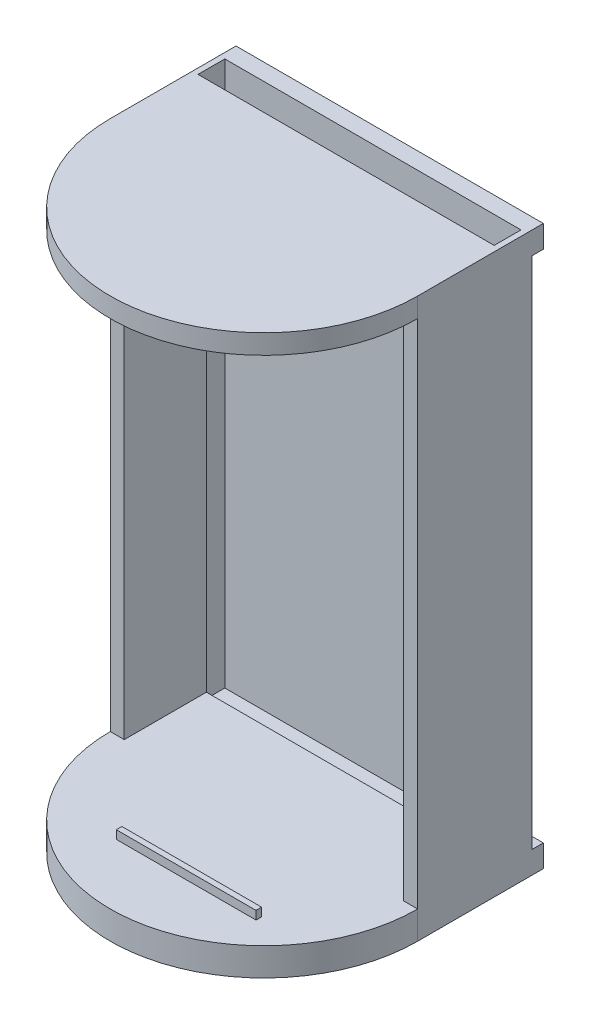
SolidWorks part; units mm, degrees
ref_plane "前基準面" through (0, 0, 0) normal (0, 0, 1) x (1, 0, 0)
ref_plane "上基準面" through (0, 0, 0) normal (0, 1, 0) x (1, 0, 0)
ref_plane "右基準面" through (0, 0, 0) normal (1, 0, 0) x (0, 0, -1)
sketch "草圖14" plane through (0, 0, 0) normal (0, 0, 1) x (1, 0, 0)
  line L0 (-52.3057, 82.5) -> (57.6943, 82.5)
  line L1 (57.6943, 82.5) -> (57.6943, -117.5)
  line L2 (57.6943, -117.5) -> (-52.3057, -117.5)
  line L3 (-52.3057, -117.5) -> (-52.3057, 82.5)
  dimension "D1" = 200
  dimension "D2" = 110
extrude "填料-伸長11" add sketch "草圖14" along normal blind 15
sketch "草圖15" plane through (0, 0, 15) normal (0, 0, 1) x (1, 0, 0)
  line L0 (-52.3057, 82.5) -> (-52.3057, -117.5)
  line L1 (-52.3057, -117.5) -> (-47.3057, -117.5)
  line L2 (57.6943, 82.5) -> (-52.3057, 82.5) construction
  line L3 (-47.3057, -117.5) -> (-47.3057, 82.5)
  line L4 (57.6943, -117.5) -> (57.6943, 82.5) construction
  line L5 (-47.3057, 82.5) -> (-52.3057, 82.5)
  line L6 (57.6943, 82.5) -> (52.6943, 82.5)
  line L7 (-52.3057, -117.5) -> (57.6943, -117.5) construction
  line L8 (52.6943, 82.5) -> (52.6943, -117.5)
  line L9 (-52.3057, 82.5) -> (-52.3057, -117.5) construction
  line L10 (52.6943, -117.5) -> (57.6943, -117.5)
  line L11 (57.6943, -117.5) -> (57.6943, 82.5)
  dimension "D4" = 5
extrude "填料-伸長12" add sketch "草圖15" along normal blind 30
sketch "草圖17" plane through (0, -117.5, 0) normal (0, -1, 0) x (1, 0, 0)
  line L0 (-52.3057, 15) -> (-52.3057, 45)
  line L1 (57.6943, 45) -> (57.6943, 15)
  line L3 (-52.3057, 45) -> (-52.3057, 0) construction
  line L4 (57.6943, 45) -> (57.6943, 0) construction
  line L6 (-52.3057, 15) -> (57.6943, 15)
  line L7 (-47.3057, 15) -> (52.6943, 15) construction
  arc A0 (-52.3057, 45) -> (57.6943, 45) centre (2.6943, 45) cw
extrude "填料-伸長14" add sketch "草圖17" against normal blind 10 separate body
sketch "草圖18" plane through (0, 82.5, 0) normal (0, 1, 0) x (1, 0, 0)
  line L0 (-52.3057, -15) -> (-52.3057, -45)
  line L1 (57.6943, -45) -> (57.6943, -15)
  line L2 (57.6943, -15) -> (-52.3057, -15)
  line L3 (52.6943, -15) -> (-47.3057, -15) construction
  line L4 (-52.3057, -45) -> (-52.3057, 0) construction
  arc A0 (-52.3057, -45) -> (57.6943, -45) centre (2.6943, -45) ccw
  arc A1 (-52.3057, -45) -> (57.6943, -45) centre (2.6943, -45) ccw construction
extrude "填料-伸長15" add sketch "草圖18" against normal blind 7
sketch "草圖19" plane through (-52.3057, 0, 0) normal (-1, 0, 0) x (0, 0, 1)
  line L0 (0, 74.5) -> (4, 74.5)
  line L1 (0, 82.5) -> (0, -117.5) construction
  line L2 (4, 74.5) -> (4, -109.5)
  line L3 (4, -109.5) -> (0, -109.5)
  line L4 (0, -109.5) -> (0, 74.5)
  line L5 (45, -117.5) -> (0, -117.5) construction
  line L6 (45, 82.5) -> (0, 82.5) construction
  dimension "D1" = 4
  dimension "D2" = 8
  dimension "D3" = 8
extrude "除料-伸長1" cut sketch "草圖19" against normal through all
sketch "草圖22" plane through (0, -107.5, 0) normal (0, 1, 0) x (1, 0, 0)
  line L0 (7.1943, -76.3382) -> (7.1943, -59.9645) construction
  line L1 (-17.8057, -75.3382) -> (32.1943, -75.3382)
  line L2 (-17.8057, -75.3382) -> (-17.8057, -77.3382)
  line L3 (-17.8057, -77.3382) -> (32.1943, -77.3382)
  line L4 (32.1943, -75.3382) -> (32.1943, -77.3382)
  line L5 (-17.8057, -75.3382) -> (32.1943, -77.3382) construction
  line L6 (-17.8057, -77.3382) -> (32.1943, -75.3382) construction
  line L7 (57.6943, -15) -> (57.6943, -45) construction
  point P0 (7.1943, -76.3382)
  dimension "D1" = 50
  dimension "D2" = 2
  dimension "D3" = 50.5
extrude "填料-伸長17" add sketch "草圖22" along normal blind 3
sketch "草圖23" plane through (0, 75.5, 0) normal (0, -1, 0) x (1, 0, 0)
  line L0 (-20.4013, 77.3382) -> (29.5987, 77.3382)
  line L1 (-20.4013, 77.3382) -> (-20.4013, 75.3382)
  line L2 (-20.4013, 75.3382) -> (29.5987, 75.3382)
  line L3 (29.5987, 77.3382) -> (29.5987, 75.3382)
  line L4 (-20.4013, 77.3382) -> (29.5987, 75.3382) construction
  line L5 (-20.4013, 75.3382) -> (29.5987, 77.3382) construction
  line L6 (-17.8057, 77.3382) -> (32.1943, 77.3382) construction
  line L7 (32.1943, 75.3382) -> (-17.8057, 75.3382) construction
  point P0 (4.5987, 76.3382)
extrude "填料-伸長18" add sketch "草圖23" along normal blind 3
sketch "草圖24" plane through (0, 82.5, 0) normal (0, 1, 0) x (1, 0, 0)
  line L1 (55.6943, -15.6) -> (-50.3057, -15.6)
  line L2 (55.6943, -15.6) -> (55.6943, -6)
  line L3 (55.6943, -6) -> (-50.3057, -6)
  line L4 (-50.3057, -15.6) -> (-50.3057, -6)
  line L5 (55.6943, -15.6) -> (-50.3057, -6) construction
  line L6 (55.6943, -6) -> (-50.3057, -15.6) construction
  line L7 (57.6943, 0) -> (57.6943, -45) construction
  line L10 (-52.3057, 0) -> (57.6943, 0) construction
  point P0 (2.6943, -10.8)
  dimension "D1" = 106
  dimension "D2" = 2
  dimension "D3" = 6
  dimension "D4" = 9.6
extrude "除料-伸長2" cut sketch "草圖24" against normal blind 195
